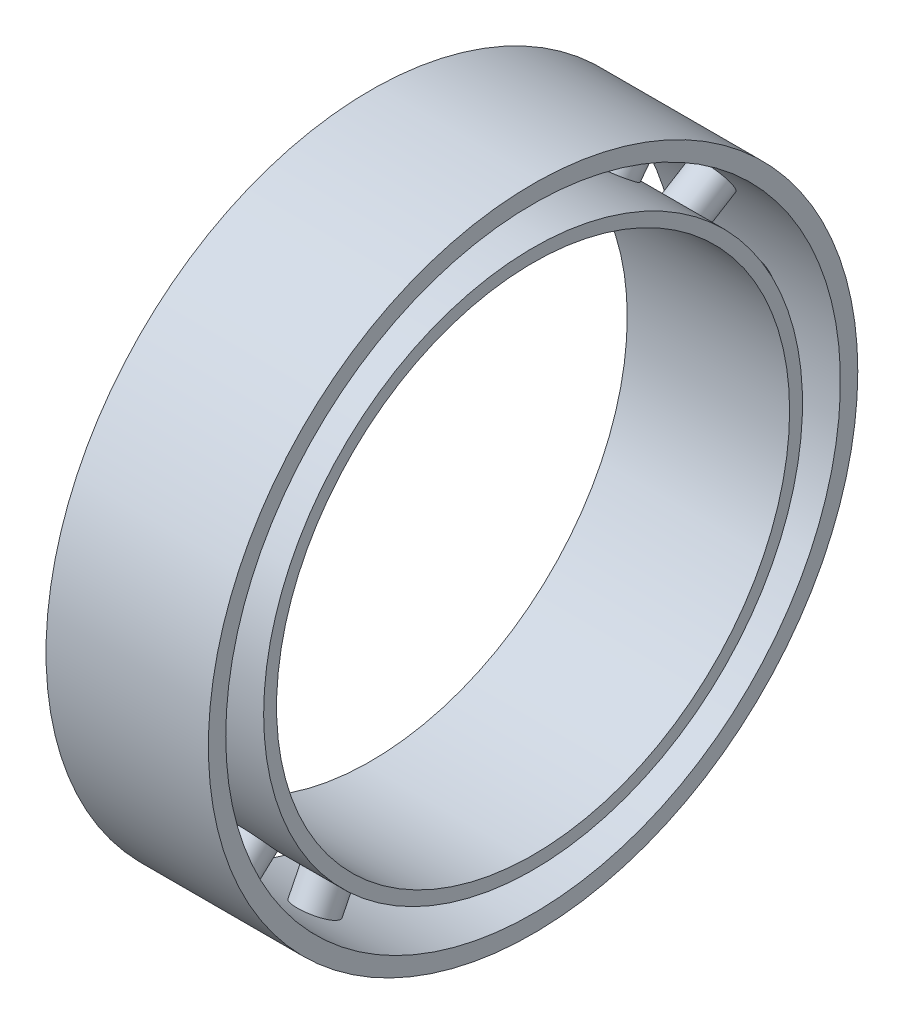
SolidWorks part; units mm, degrees
material "PBT General Purpose"
ref_plane "Front Plane" through (0, 0, 0) normal (0, 0, 1) x (1, 0, 0)
ref_plane "Top Plane" through (0, 0, 0) normal (0, 1, 0) x (1, 0, 0)
ref_plane "Right Plane" through (0, 0, 0) normal (1, 0, 0) x (0, 0, -1)
sketch "Sketch1" plane through (0, 0, 0) normal (1, 0, 0) x (0, 0, -1)
  circle A0 centre (0, 0) radius 20.066
  circle A1 centre (0, 0) radius 25.4
extrude "Boss-Extrude1" add sketch "Sketch1" along normal blind 12.7
sketch "Sketch2" plane through (0, 0, 0) normal (-1, 0, 0) x (0, 0, 1)
  circle A0 centre (0, 0) radius 21.0767
  circle A1 centre (0, 0) radius 24.041
extrude "Cut-Extrude1" cut sketch "Sketch2" against normal blind 12.7
sketch "Sketch3" plane through (0, 0, 0) normal (-1, 0, 0) x (0, 0, 1)
  line L1 (0, 21.0767) -> (2.3342, 22.4958)
  line L2 (2.3342, 22.4958) -> (0, 24.041)
  line L3 (1.2019, 24.0109) -> (3.5616, 22.4958)
  line L4 (3.5616, 22.4958) -> (1.2019, 21.0424)
  circle A0 centre (0, 0) radius 24.041 construction
  circle A1 centre (0, 0) radius 21.0767 construction
  arc A2 (0, 24.041) -> (1.2019, 24.0109) centre (0, 0) cw
  arc A3 (0, 21.0767) -> (1.2019, 21.0424) centre (0, 0) cw
extrude "Boss-Extrude2" [suppressed] add sketch "Sketch3" against normal blind 12.7
mirror "Mirror1" [suppressed] about plane through (0, 0, 0) normal (0, 0, 1)
pattern_circular "CirPattern2" [suppressed] count 15 over 360
sketch "Sketch4" plane through (0, 0, 0) normal (-1, 0, 0) x (0, 0, 1)
  line L3 (0.2578, 20.4756) -> (-0.2578, 20.4756)
  line L4 (0.2578, 20.4756) -> (0.2578, 24.3623)
  line L5 (0.2578, 24.3623) -> (-0.2578, 24.3623)
  line L6 (-0.2578, 20.4756) -> (-0.2578, 24.3623)
  line L7 (0.2578, 20.4756) -> (-0.2578, 24.3623) construction
  line L8 (0.2578, 24.3623) -> (-0.2578, 20.4756) construction
  point P0 (0, 22.419)
extrude "Boss-Extrude3" [suppressed] add sketch "Sketch4" against normal blind 12.7
pattern_circular "CirPattern3" [suppressed] count 30 over 360
ref_plane "Plane1" through (0, 0, 20.6284) normal (0, 0, 1) x (1, 0, 0)
sketch "Sketch5" plane through (0, 0, 20.6284) normal (0, 0, 1) x (1, 0, 0)
  circle A0 centre (6.35, 0) radius 1.5875
extrude "Boss-Extrude5" add sketch "Sketch5" along normal blind 4.064
pattern_circular "CirPattern4" count 17 over 360 about axis through (12.7, 0, 0) along (-1, 0, 0) of "Boss-Extrude5"
